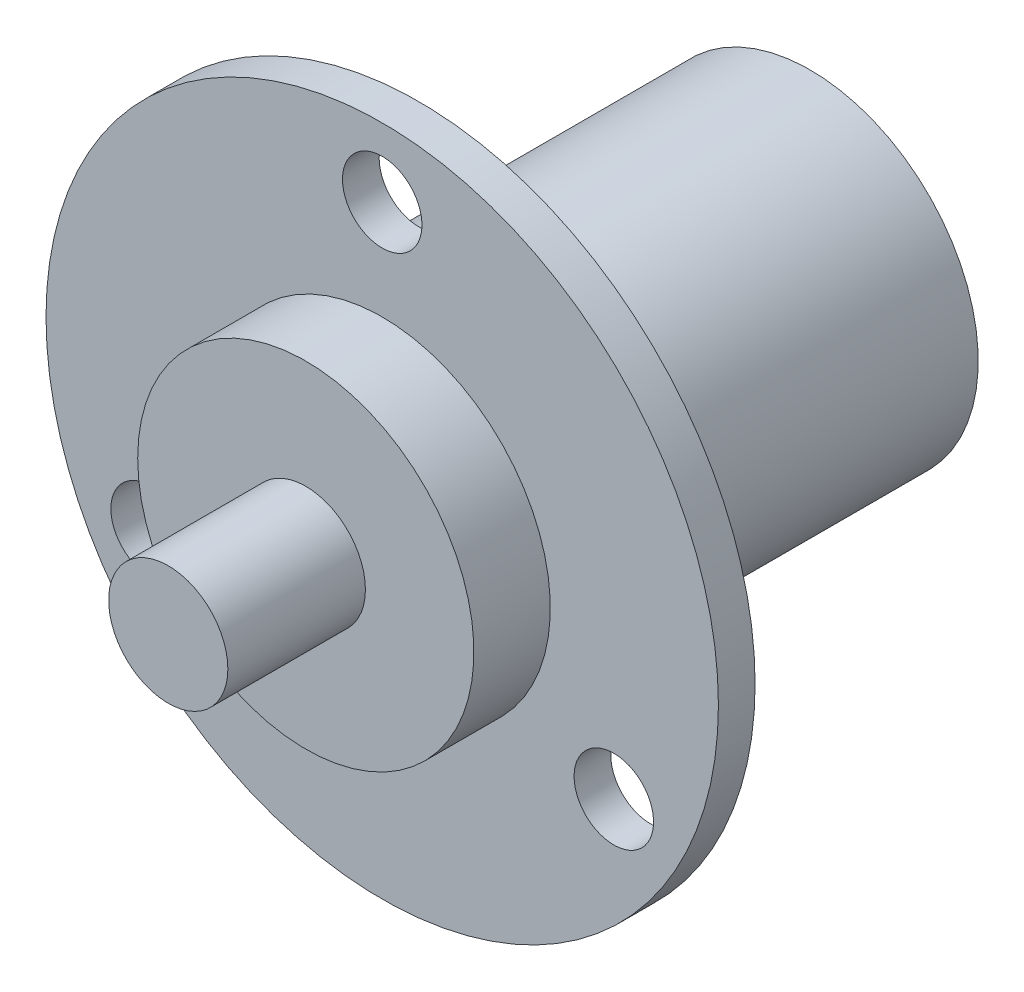
SolidWorks part; units mm, degrees
ref_plane "Front Plane" through (0, 0, 0) normal (0, 0, 1) x (1, 0, 0)
ref_plane "Top Plane" through (0, 0, 0) normal (0, 1, 0) x (1, 0, 0)
ref_plane "Right Plane" through (0, 0, 0) normal (1, 0, 0) x (0, 0, -1)
sketch "Sketch1" plane through (0, 0, 0) normal (0, 0, 1) x (1, 0, 0)
  circle A0 centre (0, 0) radius 3.9
  dimension "D1" = 7.8
extrude "Boss-Extrude1" add sketch "Sketch1" against normal blind 9
sketch "Sketch2" plane through (0, 0, -9) normal (0, 0, -1) x (-1, 0, 0)
  circle A0 centre (0, 0) radius 11
  dimension "D1" = 22
extrude "Boss-Extrude2" add sketch "Sketch2" along normal blind 5
sketch "Sketch3" plane through (0, 0, -14) normal (0, 0, -1) x (-1, 0, 0)
  circle A0 centre (0, 0) radius 22
  circle A1 centre (0, 0) radius 17.5 construction
  circle A2 centre (0, 17.5) radius 2.6
  circle A3 centre (15.1554, -8.75) radius 2.6
  circle A4 centre (-15.1554, -8.75) radius 2.6
  point P12 (0, 0)
  circle M5 centre (0, 0) radius 11
  dimension "D1" = 44
  dimension "D2" = 35
  dimension "D3" = 5.2
  dimension "D4" = 3
extrude "Boss-Extrude3" add sketch "Sketch3" along normal blind 2.4 separate body contours A0 A4 A3 A2 M5 | M5
sketch "Sketch4" plane through (0, 0, -16.4) normal (0, 0, -1) x (-1, 0, 0)
  circle A0 centre (0, 0) radius 11
  dimension "D1" = 22
extrude "Boss-Extrude4" add sketch "Sketch4" along normal blind 25.6
